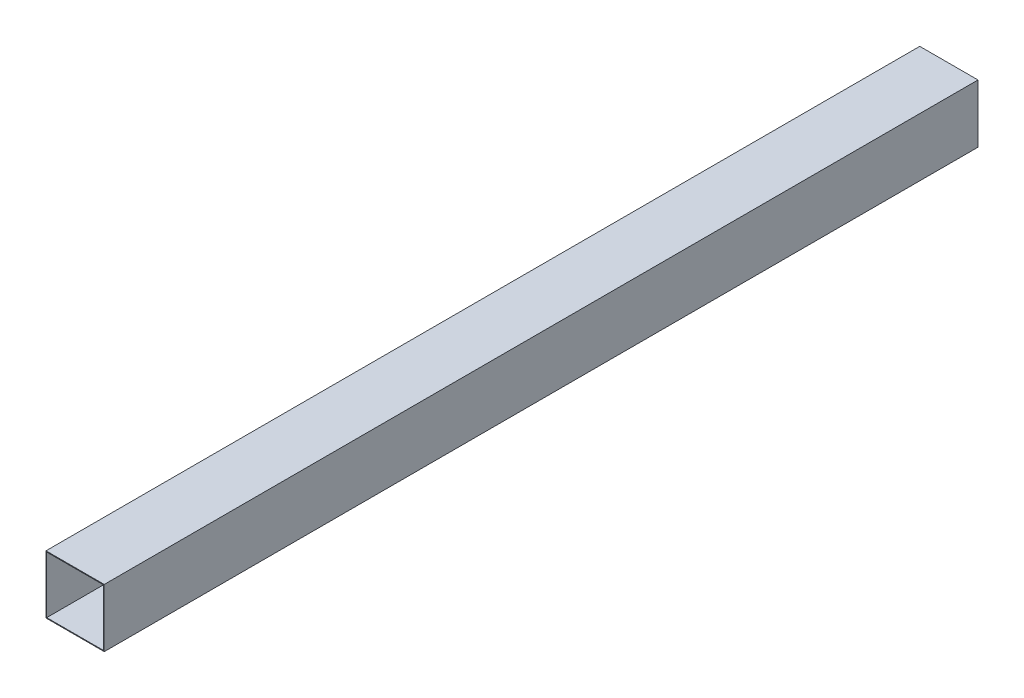
SolidWorks part; units mm, degrees
ref_plane "Alzado" through (0, 0, 0) normal (0, 0, 1) x (1, 0, 0)
ref_plane "Planta" through (0, 0, 0) normal (0, 1, 0) x (1, 0, 0)
ref_plane "Vista lateral" through (0, 0, 0) normal (1, 0, 0) x (0, 0, -1)
sketch "Croquis1" plane through (0, 0, 0) normal (0, 0, 1) x (1, 0, 0)
  line L1 (-20, 20) -> (20, 20)
  line L2 (-20, 20) -> (-20, -20)
  line L3 (-20, -20) -> (20, -20)
  line L4 (20, 20) -> (20, -20)
  line L5 (-20, 20) -> (20, -20) construction
  line L6 (-20, -20) -> (20, 20) construction
  line L7 (-19.5, 19.5) -> (19.5, 19.5)
  line L8 (-19.5, 19.5) -> (-19.5, -19.5)
  line L9 (-19.5, -19.5) -> (19.5, -19.5)
  line L10 (19.5, 19.5) -> (19.5, -19.5)
  line L11 (-19.5, 19.5) -> (19.5, -19.5) construction
  line L12 (-19.5, -19.5) -> (19.5, 19.5) construction
  point P0 (0, 0)
  point P6 (0, 0)
  dimension "D1" = 40
  dimension "D2" = 40
  dimension "D3" = 39
extrude "Saliente-Extruir1" add sketch "Croquis1" along normal blind 600
